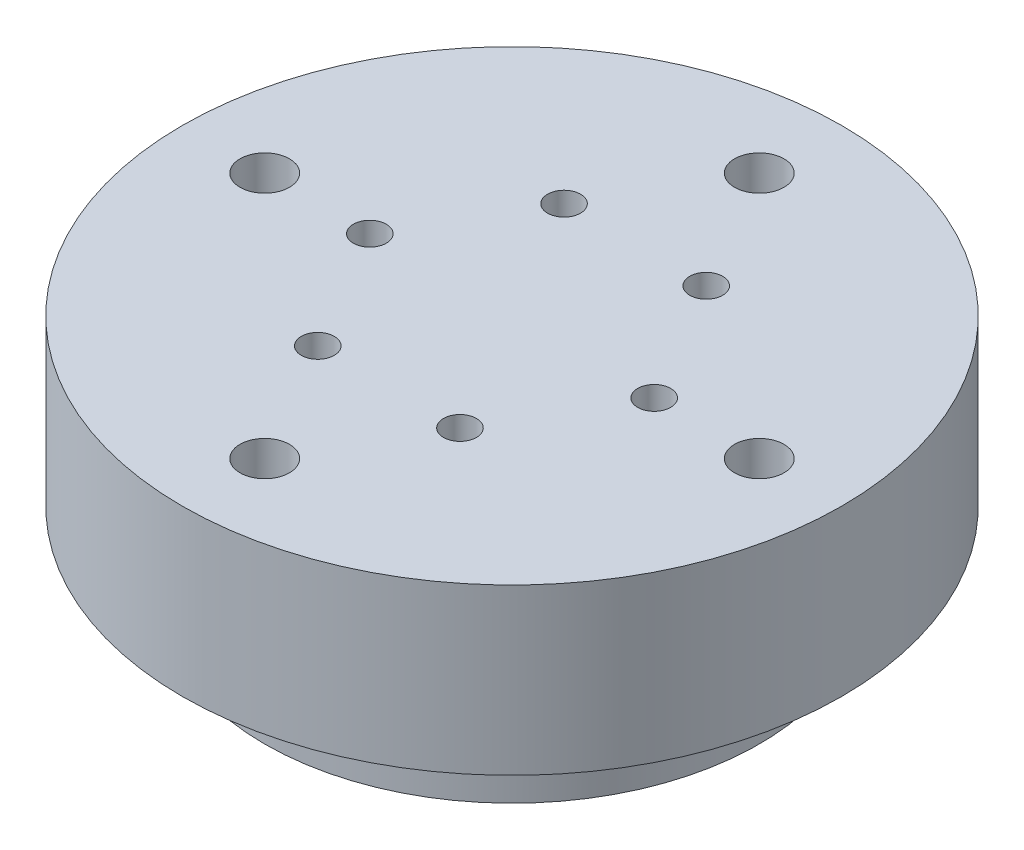
SolidWorks part; units mm, degrees
ref_plane "前视基准面" through (0, 0, 0) normal (0, 0, 1) x (1, 0, 0)
ref_plane "上视基准面" through (0, 0, 0) normal (0, 1, 0) x (1, 0, 0)
ref_plane "右视基准面" through (0, 0, 0) normal (1, 0, 0) x (0, 0, -1)
sketch "草图1" plane through (0, 0, 0) normal (0, 1, 0) x (1, 0, 0)
  circle A0 centre (0, 0) radius 30
  circle A1 centre (0, 0) radius 17.25
  circle A2 centre (-17.25, 0) radius 3
  circle A3 centre (-8.625, 14.9389) radius 3
  circle A4 centre (8.625, 14.9389) radius 3
  circle A5 centre (17.25, 0) radius 3
  circle A6 centre (8.625, -14.9389) radius 3
  circle A7 centre (-8.625, -14.9389) radius 3
  point P18 (0, 0)
  dimension "D1" = 6
extrude "凸台-拉伸1" add sketch "草图1" along normal blind 30 contours A0 A7 A1 A2 A3 A4 A5 A6 | A7 A1 A6 A5 A4 A3 A2
sketch "草图2" plane through (0, 30, 0) normal (0, 1, 0) x (1, 0, 0)
  circle A0 centre (0, 0) radius 40
  circle A1 centre (0, 0) radius 25.3726
  circle A2 centre (0, 0) radius 30
  circle A3 centre (-30, 0) radius 3
  circle A4 centre (0, 30) radius 3
  circle A5 centre (30, 0) radius 3
  circle A6 centre (0, -30) radius 3
  point P15 (0, 0)
  dimension "D1" = 4
extrude "凸台-拉伸2" add sketch "草图2" against normal blind 20 contours A0 A6 A2 A3 A4 A5 | A6 A2 A5 A4 A3 A1
sketch "草图3" plane through (0, 30, 0) normal (0, 1, 0) x (1, 0, 0)
  circle A0 centre (0, 0) radius 30
  circle A1 centre (-30, 0) radius 3
  circle A2 centre (0, 30) radius 3
  circle A3 centre (30, 0) radius 3
  circle A4 centre (0, -30) radius 3
  point P14 (0, 0)
  arc M3 (29.85, -2.9962) -> (29.85, 2.9962) centre (0, 0) ccw
  arc M5 (2.9962, 29.85) -> (-2.9962, 29.85) centre (0, 0) ccw
  arc M7 (-29.85, 2.9962) -> (-29.85, -2.9962) centre (0, 0) ccw
  arc M8 (-2.9962, -29.85) -> (2.9962, -29.85) centre (0, 0) ccw
  dimension "D1" = 4
extrude "切除-拉伸1" cut sketch "草图3" against normal blind 20 contours A3 M3 | A2 M5 | A4 M8 | A1 M7
sketch "草图4" plane through (0, 30, 0) normal (0, 1, 0) x (1, 0, 0)
  circle A0 centre (0, 0) radius 17.25
  circle A1 centre (0, 0) radius 25.3726
  circle A2 centre (8.625, 14.9389) radius 2
  circle A3 centre (17.25, 0) radius 2
  circle A4 centre (8.625, -14.9389) radius 2
  circle A5 centre (-8.625, -14.9389) radius 2
  circle A6 centre (-17.25, 0) radius 2
  circle A7 centre (-8.625, 14.9389) radius 2
  point P20 (0, 0)
  circle M5 centre (8.625, -14.9389) radius 3
  circle M6 centre (17.25, 0) radius 3
  circle M7 centre (8.625, 14.9389) radius 3
  circle M8 centre (-8.625, 14.9389) radius 3
  circle M9 centre (-17.25, 0) radius 3
  circle M10 centre (-8.625, -14.9389) radius 3
  dimension "D1" = 6
extrude "凸台-拉伸4" add sketch "草图4" against normal blind 30 contours A6 A0 M9 | A6 A0 M9 | A5 A0 M10 | A5 A0 M10 | A4 A0 M5 | A4 A0 M5 | A3 A0 M6 | A3 A0 M6 | A2 A0 M7 | A2 A0 M7 | A7 A0 M8 | A7 A0 M8
